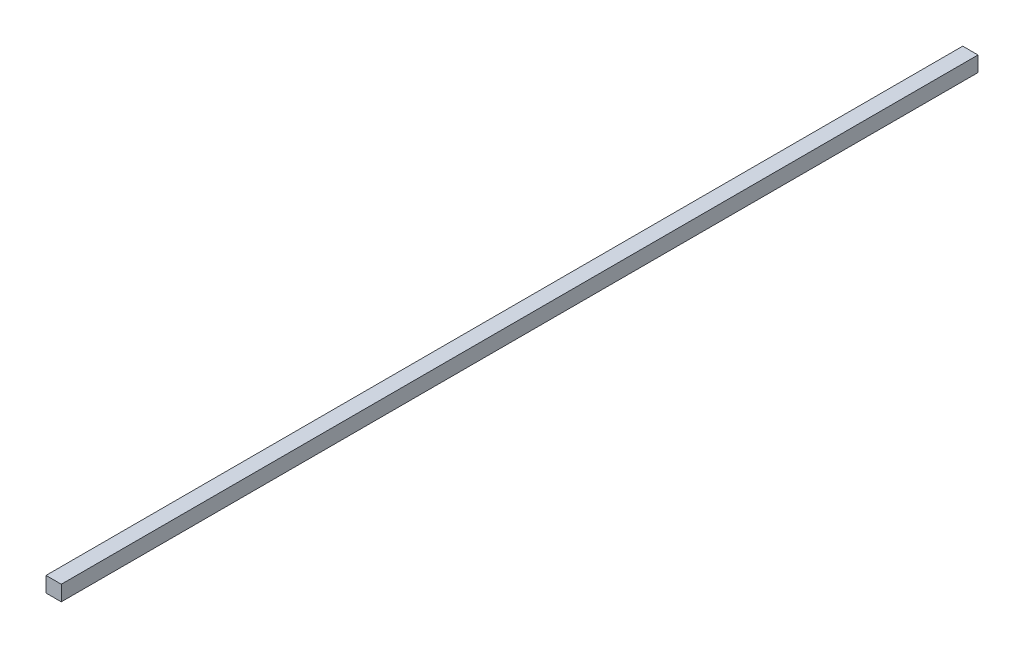
SolidWorks part; units mm, degrees
ref_plane "Front Plane" through (0, 0, 0) normal (0, 0, 1) x (1, 0, 0)
ref_plane "Top Plane" through (0, 0, 0) normal (0, 1, 0) x (1, 0, 0)
ref_plane "Right Plane" through (0, 0, 0) normal (1, 0, 0) x (0, 0, -1)
sketch "Sketch1" plane through (0, 0, 0) normal (0, 0, 1) x (1, 0, 0)
  line L1 (0, 0) -> (10, 0)
  line L2 (0, 0) -> (0, -10)
  line L3 (0, -10) -> (10, -10)
  line L4 (10, 0) -> (10, -10)
  dimension "D1" = 10
extrude "Boss-Extrude1" add sketch "Sketch1" along normal blind 600
sketch "Sketch2" plane through (0, -10, 0) normal (0, -1, 0) x (1, 0, 0)
  line L0 (0, 192.9085) -> (10, 188.5467)
  line L1 (0, 600) -> (0, 0) construction
  line L2 (10, 600) -> (10, 0) construction
  line L3 (10, 188.5467) -> (10, 600)
  line L4 (10, 600) -> (0, 600)
  line L5 (0, 600) -> (0, 192.9085)
